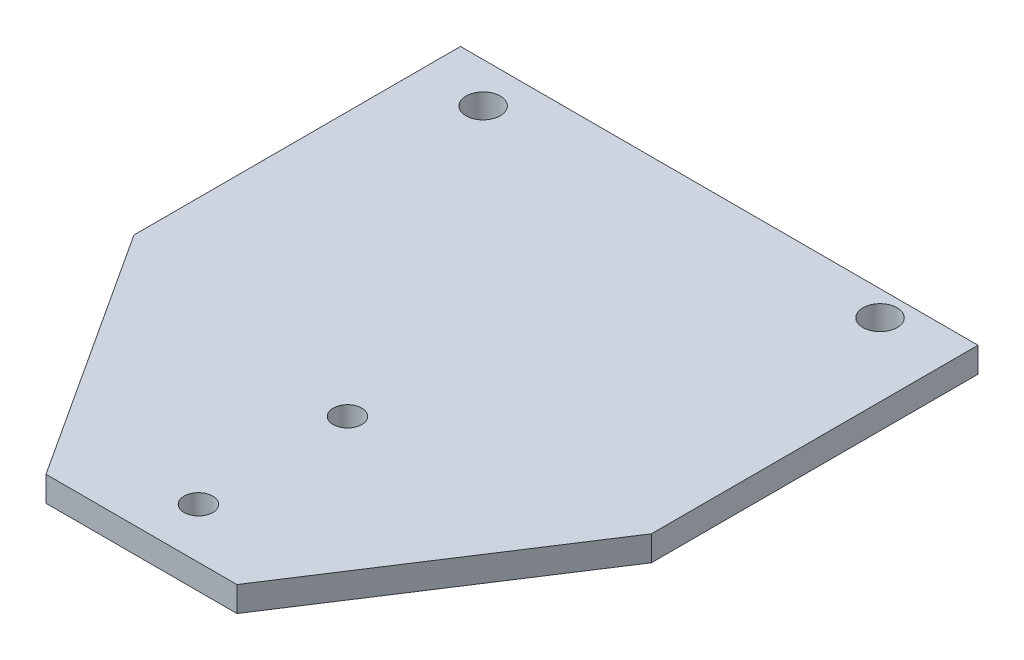
SolidWorks part; units mm, degrees
ref_plane "Front Plane" through (0, 0, 0) normal (0, 0, 1) x (1, 0, 0)
ref_plane "Top Plane" through (0, 0, 0) normal (0, 1, 0) x (1, 0, 0)
ref_plane "Right Plane" through (0, 0, 0) normal (1, 0, 0) x (0, 0, -1)
sketch "Sketch1" plane through (0, 0, 0) normal (0, 1, 0) x (1, 0, 0)
  line L0 (51.5, 65) -> (51.5, 0) construction
  line L2 (0, 0) -> (0, 65)
  line L4 (103, 0) -> (103, 65)
  line L5 (32.5, -50) -> (70.5, -50)
  line L6 (32.5, -50) -> (0, 0)
  line L7 (70.5, -50) -> (103, 0)
  line L8 (51.5, 0) -> (51.5, -50) construction
  line L12 (0, 65) -> (103, 65)
  circle A1 centre (88.5, 60) radius 3.4151
  circle A5 centre (12.5, 57) radius 3.415
  dimension "D4" = 6.8302
  dimension "D2" = 6.83
  dimension "D1" = 103
  dimension "D6" = 39
  dimension "D7" = 19
  dimension "D8" = 50
  dimension "D9" = 37
extrude "Boss-Extrude1" add sketch "Sketch1" along normal blind 5
sketch "Sketch2" plane through (0, 5, 0) normal (0, 1, 0) x (1, 0, 0)
  line L0 (52.9511, -50) -> (51.5, 82)
  line L1 (32.5, -50) -> (70.5, -50) construction
  line L2 (103, 82) -> (0, 82) construction
  circle A0 centre (52.8412, -40) radius 2.85
  circle A1 centre (52.5114, -10) radius 2.85
  dimension "D1" = 5.7
  dimension "D2" = 5.7
  dimension "D3" = 30
  dimension "D4" = 10
extrude "Cut-Extrude1" cut sketch "Sketch2" against normal through all both and the other way through all contours A1 | A0
